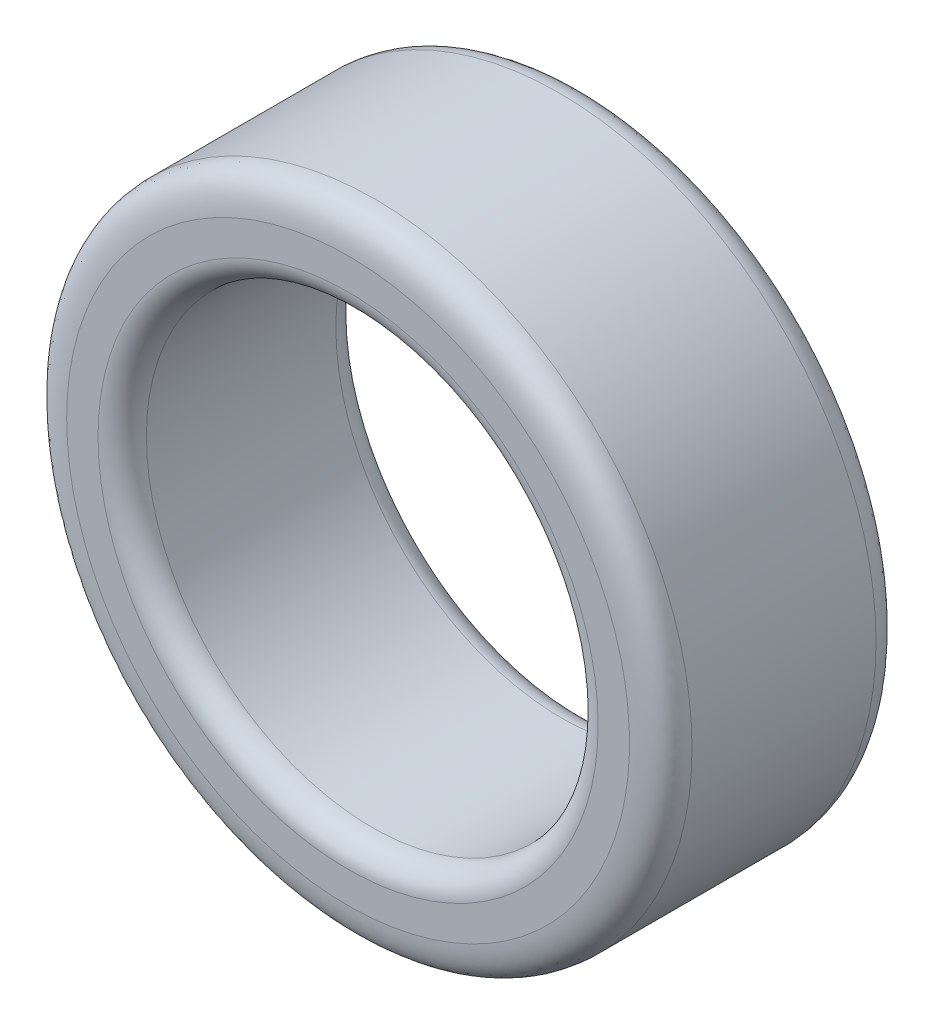
SolidWorks part; units mm, degrees
ref_plane "Plan de face" through (0, 0, 0) normal (0, 0, 1) x (1, 0, 0)
ref_plane "Plan de dessus" through (0, 0, 0) normal (0, 1, 0) x (1, 0, 0)
ref_plane "Plan de droite" through (0, 0, 0) normal (1, 0, 0) x (0, 0, -1)
sketch "Esquisse1" plane through (0, 0, 0) normal (0, 0, 1) x (1, 0, 0)
  circle A0 centre (0, 0) radius 80
  circle A1 centre (0, 0) radius 57
  dimension "D1" = 114
  dimension "D2" = 160
extrude "Boss.-Extru.1" add sketch "Esquisse1" along normal blind 46.43
sketch "Esquisse2" plane through (0, 0, 0) normal (1, 0, 0) x (0, 0, -1)
  line L0 (0, 57) -> (0.689, 57)
  line L1 (6.79, 63.101) -> (6.79, 64)
  line L2 (6.79, 64) -> (6.79, 71.0153)
  line L3 (0, 57) -> (0, 80) construction
  line L4 (-46.43, 57) -> (-47.119, 57)
  line L5 (0, 80) -> (0, 57)
  line L6 (0, 0) -> (-46.43, 0) construction
  line L7 (-46.43, 80) -> (-46.43, -80) construction
  line L8 (-23.215, 0) -> (-23.215, 84.2082) construction
  line L9 (-46.43, 57) -> (-46.43, 80) construction
  line L10 (-46.43, 80) -> (-46.43, 57)
  line L12 (-53.22, 64) -> (-53.22, 71.0153)
  line L13 (-53.22, 63.101) -> (-53.22, 64)
  arc A0 (0.689, 57) -> (6.79, 63.101) centre (0.689, 63.101) ccw
  arc A1 (-47.119, 57) -> (-53.22, 63.101) centre (-47.119, 63.101) cw
  spline S0 degree 3 poles (6.79, 71.0153) (6.4467, 77.9043) (4.024, 79.8493) (0, 80) knots 0 0 0 0 1 1 1 1
  spline S1 degree 3 poles (-53.22, 71.0153) (-52.8767, 77.9043) (-50.454, 79.8493) (-46.43, 80) knots 0 0 0 0 1 1 1 1
  point P0 (0, 80)
  point P1 (-46.43, 80)
  point P3 (-46.43, 57)
  point P5 (0, 57)
  point P7 (0, -57)
  point P9 (0, -80)
  point P11 (-46.43, -80)
  point P13 (-46.43, -57)
  point P25 (6.79, 57)
  point P42 (-53.22, 57)
  dimension "D3" = 6.101
  dimension "D1" = 6.79
  dimension "D2" = 7
revolve "Révolution1" add sketch "Esquisse2" angle 360 about L6
